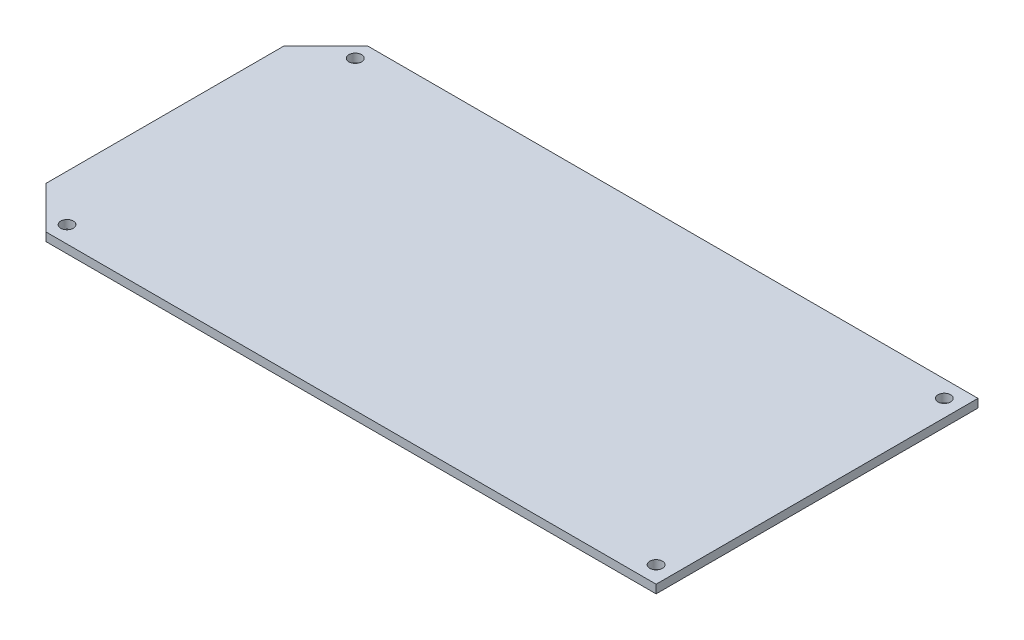
SolidWorks part; units mm, degrees
ref_plane "Front Plane" through (0, 0, 0) normal (0, 0, 1) x (1, 0, 0)
ref_plane "Top Plane" through (0, 0, 0) normal (0, 1, 0) x (1, 0, 0)
ref_plane "Right Plane" through (0, 0, 0) normal (1, 0, 0) x (0, 0, -1)
sketch "Sketch1" plane through (0, 0, 0) normal (0, 1, 0) x (1, 0, 0)
  line L1 (-77.5, -38.25) -> (77.5, -38.25)
  line L2 (-77.5, -38.25) -> (-77.5, 38.25)
  line L3 (-77.5, 38.25) -> (77.5, 38.25)
  line L4 (77.5, -38.25) -> (77.5, 38.25)
  line L5 (-77.5, -38.25) -> (77.5, 38.25) construction
  line L6 (-77.5, 38.25) -> (77.5, -38.25) construction
  point P0 (0, 0)
  dimension "D1" = 155
  dimension "D2" = 76.5
extrude "Boss-Extrude1" add sketch "Sketch1" along normal blind 2
sketch "Sketch2" plane through (0, 2, 0) normal (0, 1, 0) x (1, 0, 0)
  line L0 (77.5, 38.25) -> (-77.5, 38.25) construction
  line L1 (77.5, -38.25) -> (77.5, 38.25) construction
  circle A0 centre (73.5, 34.25) radius 1.5
  circle A1 centre (73.5, -34.25) radius 1.5
  circle A2 centre (-66.5, -34.25) radius 1.5
  circle A3 centre (-66.5, 34.25) radius 1.5
  dimension "D1" = 3
  dimension "D2" = 3
  dimension "D3" = 68.5
  dimension "D4" = 4
  dimension "D5" = 4
  dimension "D6" = 140
extrude "Cut-Extrude1" cut sketch "Sketch2" against normal through all
chamfer "Chamfer1" distance 10 angle 45 2 edges at (-77.5, 1, 38.25) (-77.5, 1, -38.25)
